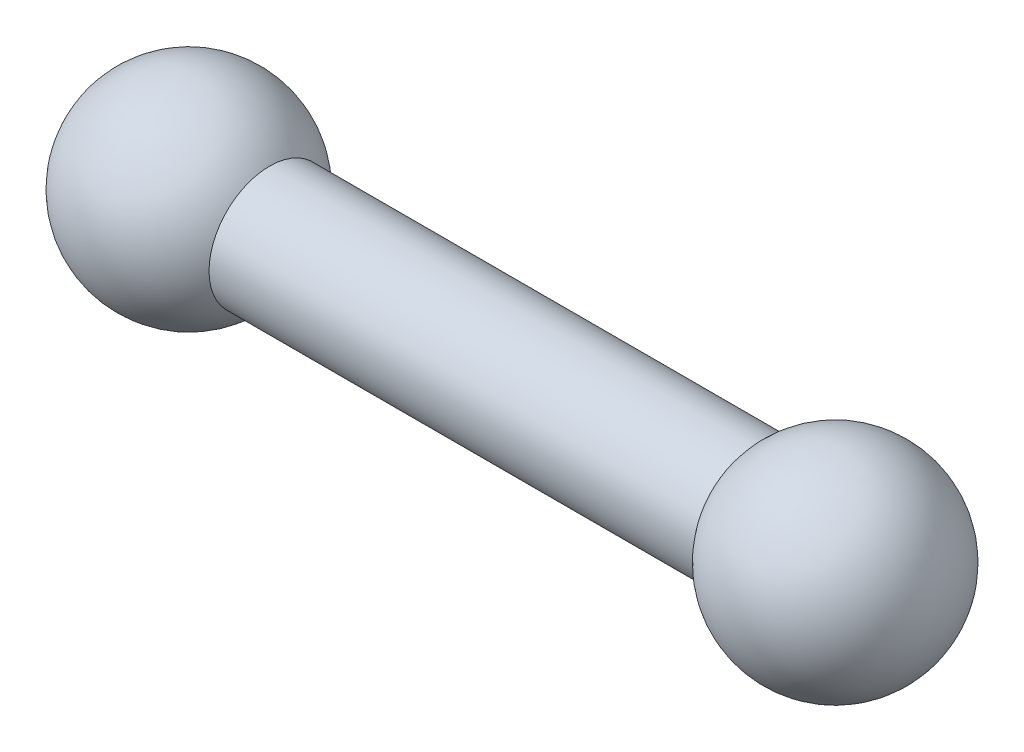
SolidWorks part; units mm, degrees
ref_plane "Front Plane" through (0, 0, 0) normal (0, 0, 1) x (1, 0, 0)
ref_plane "Top Plane" through (0, 0, 0) normal (0, 1, 0) x (1, 0, 0)
ref_plane "Right Plane" through (0, 0, 0) normal (1, 0, 0) x (0, 0, -1)
sketch "Sketch1" plane through (0, 0, 0) normal (0, 0, 1) x (1, 0, 0)
  line L0 (0, 0) -> (16, 0) construction
  line L1 (2, 1.5) -> (14, 1.5) construction
  line L2 (-2.5, 0) -> (18.5, 0)
  line L3 (2, 1.5) -> (14, 1.5)
  circle A0 centre (0, 0) radius 2.5 construction
  circle A1 centre (16, 0) radius 2.5 construction
  arc A2 (18.5, 0) -> (14, 1.5) centre (16, 0) ccw
  arc A3 (-2.5, 0) -> (2, 1.5) centre (0, 0) cw
  dimension "D1" = 16
  dimension "D2" = 5
  dimension "D3" = 1.5
revolve "Revolve1" add sketch "Sketch1" angle 360 about L2
